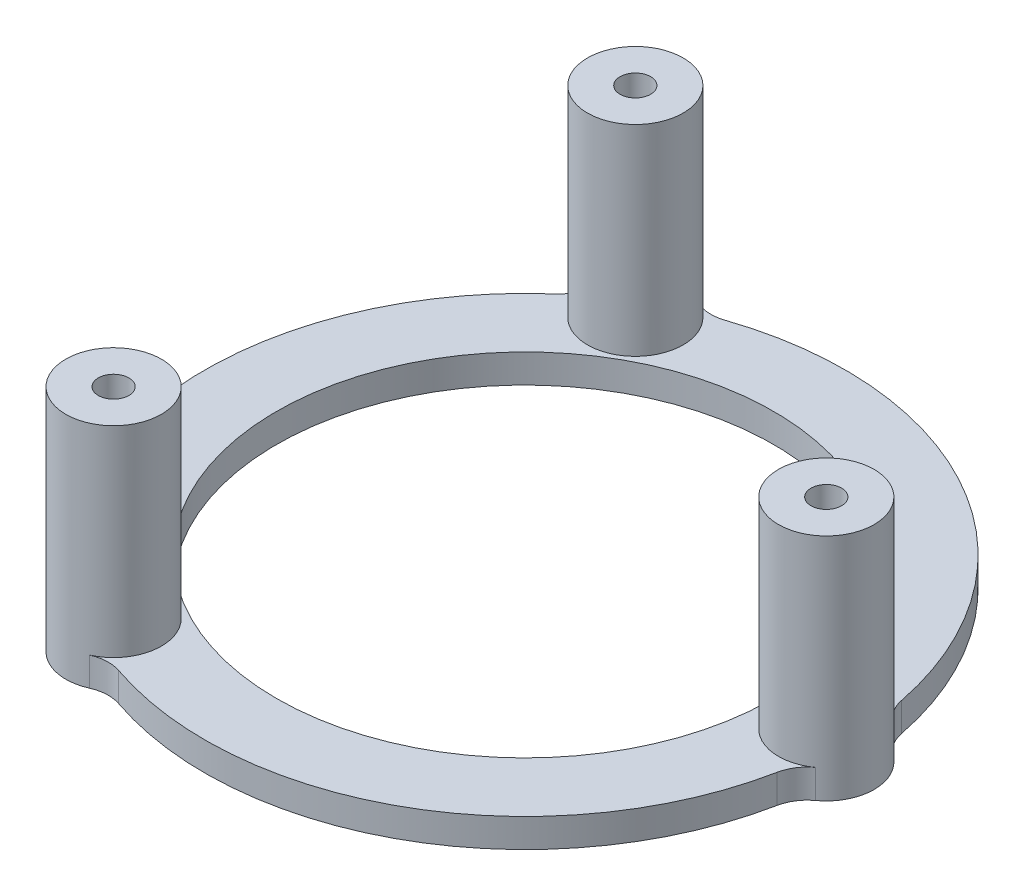
SolidWorks part; units mm, degrees
material "7075-O (SS)"
ref_plane "前视基准面" through (0, 0, 0) normal (0, 0, 1) x (1, 0, 0)
ref_plane "上视基准面" through (0, 0, 0) normal (0, 1, 0) x (1, 0, 0)
ref_plane "右视基准面" through (0, 0, 0) normal (1, 0, 0) x (0, 0, -1)
sketch "草图1" plane through (0, 0, 0) normal (0, 1, 0) x (1, 0, 0)
  line L0 (21.1488, 0) -> (-21.1488, 0) construction
  line L1 (0, -20.3203) -> (0, 20.3203) construction
  circle A0 centre (0, 0) radius 15.75 construction
  circle A1 centre (15.75, 0) radius 2.5 construction
  circle A2 centre (0, 0) radius 13
  circle A3 centre (0, 0) radius 18.5
  point P5 (0, 0)
  point P9 (0, 0)
  dimension "D1" = 31.5
  dimension "D2" = 5
  dimension "D3" = 26
  dimension "D4" = 37
extrude "凸台-拉伸1" add sketch "草图1" along normal blind 1.5
sketch "草图2" plane through (0, 1.5, 0) normal (0, 1, 0) x (1, 0, 0)
  line L0 (22.233, 0) -> (-22.233, 0) construction
  line L1 (0, -21.8238) -> (0, 21.8238) construction
  circle A0 centre (15.75, 0) radius 2.5
  circle A1 centre (0, 0) radius 15.75 construction
  circle A2 centre (-7.875, -13.6399) radius 2.5
  circle A3 centre (-7.875, 13.6399) radius 2.5
  point P4 (0, 0)
  point P16 (0, 0)
  dimension "D1" = 5
  dimension "D3" = 3
extrude "凸台-拉伸2" add sketch "草图2" along normal blind 10.5
hole_wizard "M2 螺纹孔1" positions "3D草图1" profile "草图3" tap size "M2" standard "GB"
sketch3d "3D草图1"
  line L0 (15.75, 12, 0) -> (15.75, 1.5, 0) construction
  line L1 (-7.875, 12, -13.6399) -> (-7.875, 1.5, -13.6399) construction
  line L2 (-7.875, 12, 13.6399) -> (-7.875, 1.5, 13.6399) construction
  point P0 (15.75, 12, 0)
  point P4 (-7.875, 12, -13.6399)
  point P8 (-7.875, 12, 13.6399)
sketch "草图3" plane through (15.75, 12, 0) normal (1, 0, 0) x (0, 0, 1)
  line L0 (0, 0) -> (0, 7.4807)
  line L1 (0, 7.4807) -> (0.8, 7)
  line L2 (0.8, 7) -> (0.8, 0)
  line L5 (0.8, 0) -> (0, 0)
  line L10 (0, 7.4807) -> (-0.8, 7) construction
  line L11 (0, -6.35) -> (0, 107.95) construction
  dimension "螺纹孔钻头直径" = 1.6
  dimension "螺纹孔钻头深度" = 7
  dimension "导头角度" = 118
cosmetic thread "孔螺蚊线1" parameters "D1"=5, "D2"=2
cosmetic thread "孔螺蚊线2" parameters "D1"=5, "D2"=2
cosmetic thread "孔螺蚊线3" parameters "D1"=5, "D2"=2
sketch "草图4" plane through (0, 1.5, 0) normal (0, 1, 0) x (1, 0, 0)
  arc A0 (16.5833, 2.357) -> (-6.2504, 15.5401) centre (0, 0) ccw
  circle A1 centre (-7.875, -13.6399) radius 2.5 construction
  circle A2 centre (-7.875, 13.6399) radius 2.5 construction
  circle A3 centre (15.75, 0) radius 2.5 construction
  arc A4 (-10.3329, -13.1831) -> (-6.2504, -15.5401) centre (-7.875, -13.6399) ccw
  arc A5 (-6.2504, 15.5401) -> (-10.3329, 13.1831) centre (-7.875, 13.6399) ccw
  arc A6 (16.5833, -2.357) -> (16.5833, 2.357) centre (15.75, 0) ccw
  arc A7 (-6.2504, -15.5401) -> (16.5833, -2.357) centre (0, 0) ccw
  arc A8 (-10.3329, 13.1831) -> (-10.3329, -13.1831) centre (0, 0) ccw
  dimension "D1" = 33.5
extrude "切除-拉伸1" cut sketch "草图4" against normal blind 10 flip side to cut
fillet "圆角1" radius 2 6 edges at (16.5833, 0.75, 2.357) (16.5833, 0.75, -2.357) (-10.3329, 0.75, -13.1831) (-10.3329, 0.75, 13.1831) (-6.2504, 0.75, 15.5401) (-6.2504, 0.75, -15.5401)
sketch "草图5" plane through (0, 0, 0) normal (0, -1, 0) x (1, 0, 0)
  arc A0 (21.5757, 7.2147) -> (-4.5397, 22.2924) centre (0, 0) ccw
  arc A2 (-7.2594, 22.1176) -> (-15.5247, 17.3456) centre (-7.875, 13.6399) ccw
  arc A4 (-17.036, 15.0778) -> (-17.036, -15.0778) centre (0, 0) ccw
  arc A6 (-15.5247, -17.3456) -> (-7.2594, -22.1176) centre (-7.875, -13.6399) ccw
  arc A8 (-4.5397, -22.2924) -> (21.5757, -7.2147) centre (0, 0) ccw
  arc A10 (22.7841, -4.7719) -> (22.7841, 4.7719) centre (15.75, 0) ccw
  arc A12 (16.431, 3.2537) -> (-5.3977, 15.8565) centre (0, 0) ccw
  arc A13 (-6.8568, 15.9232) -> (-5.3977, 15.8565) centre (-6.0422, 17.7498) ccw
  arc A14 (-6.8568, 15.9232) -> (-10.3615, 13.8997) centre (-7.875, 13.6399) ccw
  arc A15 (-11.0332, 12.6028) -> (-10.3615, 13.8997) centre (-12.3506, 14.1076) ccw
  arc A16 (-11.0332, 12.6028) -> (-11.0332, -12.6028) centre (0, 0) ccw
  arc A17 (-10.3615, -13.8997) -> (-11.0332, -12.6028) centre (-12.3506, -14.1076) ccw
  arc A18 (-10.3615, -13.8997) -> (-6.8568, -15.9232) centre (-7.875, -13.6399) ccw
  arc A19 (-5.3977, -15.8565) -> (-6.8568, -15.9232) centre (-6.0422, -17.7498) ccw
  arc A20 (-5.3977, -15.8565) -> (16.431, -3.2537) centre (0, 0) ccw
  arc A21 (17.2183, -2.0234) -> (16.431, -3.2537) centre (18.3929, -3.6422) ccw
  arc A22 (17.2183, -2.0234) -> (17.2183, 2.0234) centre (15.75, 0) ccw
  arc A23 (16.431, 3.2537) -> (17.2183, 2.0234) centre (18.3929, 3.6422) ccw
  arc A24 (16.431, 3.2537) -> (-5.3977, 15.8565) centre (0, 0) ccw construction
  arc A25 (-6.8568, 15.9232) -> (-5.3977, 15.8565) centre (-6.0422, 17.7498) ccw construction
  arc A26 (-6.8568, 15.9232) -> (-10.3615, 13.8997) centre (-7.875, 13.6399) ccw construction
  arc A27 (-11.0332, 12.6028) -> (-10.3615, 13.8997) centre (-12.3506, 14.1076) ccw construction
  arc A28 (-11.0332, 12.6028) -> (-11.0332, -12.6028) centre (0, 0) ccw construction
  arc A29 (-10.3615, -13.8997) -> (-11.0332, -12.6028) centre (-12.3506, -14.1076) ccw construction
  arc A30 (-10.3615, -13.8997) -> (-6.8568, -15.9232) centre (-7.875, -13.6399) ccw construction
  arc A31 (-5.3977, -15.8565) -> (-6.8568, -15.9232) centre (-6.0422, -17.7498) ccw construction
  arc A32 (-5.3977, -15.8565) -> (16.431, -3.2537) centre (0, 0) ccw construction
  arc A33 (17.2183, -2.0234) -> (16.431, -3.2537) centre (18.3929, -3.6422) ccw construction
  arc A34 (17.2183, -2.0234) -> (17.2183, 2.0234) centre (15.75, 0) ccw construction
  arc A35 (16.431, 3.2537) -> (17.2183, 2.0234) centre (18.3929, 3.6422) ccw construction
  arc A36 (-15.9838, 16.1889) -> (-15.9838, 16.1889) centre (-15.9838, 16.1889) ccw construction
  arc A37 (-6.0281, 21.9368) -> (-6.0281, 21.9368) centre (-6.0281, 21.9368) ccw construction
  arc A38 (22.0119, 5.7479) -> (22.0119, 5.7479) centre (22.0119, 5.7479) ccw construction
  arc A39 (22.0119, -5.7479) -> (22.0119, -5.7479) centre (22.0119, -5.7479) ccw construction
  arc A40 (-6.0281, -21.9368) -> (-6.0281, -21.9368) centre (-6.0281, -21.9368) ccw construction
  arc A41 (-15.9838, -16.1889) -> (-15.9838, -16.1889) centre (-15.9838, -16.1889) ccw construction
  arc A42 (22.0119, -5.7479) -> (22.0119, 5.7479) centre (15.75, 0) ccw construction
  arc A43 (22.0119, 5.7479) -> (-6.0281, 21.9368) centre (0, 0) ccw construction
  arc A44 (22.7841, 4.7719) -> (21.5757, 7.2147) centre (31.0595, 10.386) cw
  arc A45 (-6.0281, 21.9368) -> (-15.9838, 16.1889) centre (-7.875, 13.6399) ccw construction
  arc A46 (-4.5397, 22.2924) -> (-7.2594, 22.1176) centre (-6.5352, 32.0913) cw
  arc A47 (-15.9838, 16.1889) -> (-15.9838, -16.1889) centre (0, 0) ccw construction
  arc A48 (-17.036, 15.0778) -> (-15.5247, 17.3456) centre (-24.5243, 21.7053) ccw
  arc A49 (-15.9838, -16.1889) -> (-6.0281, -21.9368) centre (-7.875, -13.6399) ccw construction
  arc A50 (-17.036, -15.0778) -> (-15.5247, -17.3456) centre (-24.5243, -21.7053) cw
  arc A51 (-6.0281, -21.9368) -> (22.0119, -5.7479) centre (0, 0) ccw construction
  arc A52 (-7.2594, -22.1176) -> (-4.5397, -22.2924) centre (-6.5352, -32.0913) cw
  arc A53 (21.5757, -7.2147) -> (22.7841, -4.7719) centre (31.0595, -10.386) cw
  dimension "D3" = 10
  dimension "D1" = 0
  dimension "D2" = 6
sketch "草图6" plane through (0, 1.5, 0) normal (0, 1, 0) x (1, 0, 0)
  arc A12 (21.5757, 7.2147) -> (22.7841, 4.7719) centre (31.0595, 10.386) ccw
  arc A13 (21.5757, 7.2147) -> (-4.5397, 22.2924) centre (0, 0) ccw
  arc A14 (-7.2594, 22.1176) -> (-4.5397, 22.2924) centre (-6.5352, 32.0913) ccw
  arc A15 (-7.2594, 22.1176) -> (-15.5247, 17.3456) centre (-7.875, 13.6399) ccw
  arc A16 (-17.036, 15.0778) -> (-15.5247, 17.3456) centre (-24.5243, 21.7053) ccw
  arc A17 (-17.036, 15.0778) -> (-17.036, -15.0778) centre (0, 0) ccw
  arc A18 (-15.5247, -17.3456) -> (-17.036, -15.0778) centre (-24.5243, -21.7053) ccw
  arc A19 (-15.5247, -17.3456) -> (-7.2594, -22.1176) centre (-7.875, -13.6399) ccw
  arc A20 (-4.5397, -22.2924) -> (-7.2594, -22.1176) centre (-6.5352, -32.0913) ccw
  arc A21 (-4.5397, -22.2924) -> (21.5757, -7.2147) centre (0, 0) ccw
  arc A22 (22.7841, -4.7719) -> (21.5757, -7.2147) centre (31.0595, -10.386) ccw
  arc A23 (22.7841, -4.7719) -> (22.7841, 4.7719) centre (15.75, 0) ccw
  arc A24 (21.5757, 7.2147) -> (22.7841, 4.7719) centre (31.0595, 10.386) ccw
  arc A25 (21.5757, 7.2147) -> (-4.5397, 22.2924) centre (0, 0) ccw
  arc A26 (-7.2594, 22.1176) -> (-4.5397, 22.2924) centre (-6.5352, 32.0913) ccw
  arc A27 (-7.2594, 22.1176) -> (-15.5247, 17.3456) centre (-7.875, 13.6399) ccw
  arc A28 (-17.036, 15.0778) -> (-15.5247, 17.3456) centre (-24.5243, 21.7053) ccw
  arc A29 (-17.036, 15.0778) -> (-17.036, -15.0778) centre (0, 0) ccw
  arc A30 (-15.5247, -17.3456) -> (-17.036, -15.0778) centre (-24.5243, -21.7053) ccw
  arc A31 (-15.5247, -17.3456) -> (-7.2594, -22.1176) centre (-7.875, -13.6399) ccw
  arc A32 (-4.5397, -22.2924) -> (-7.2594, -22.1176) centre (-6.5352, -32.0913) ccw
  arc A33 (-4.5397, -22.2924) -> (21.5757, -7.2147) centre (0, 0) ccw
  arc A34 (22.7841, -4.7719) -> (21.5757, -7.2147) centre (31.0595, -10.386) ccw
  arc A35 (22.7841, -4.7719) -> (22.7841, 4.7719) centre (15.75, 0) ccw
  dimension "D1" = 0
sketch "草图7" plane through (0, 12, 0) normal (0, 1, 0) x (1, 0, 0)
  circle A0 centre (-7.875, -13.6399) radius 0.8 construction
  circle A1 centre (15.75, 0) radius 0.8 construction
  circle A2 centre (-7.875, 13.6399) radius 0.8 construction
  circle A3 centre (-7.875, -13.6399) radius 0.8
  circle A4 centre (15.75, 0) radius 0.8
  circle A5 centre (-7.875, 13.6399) radius 0.8
